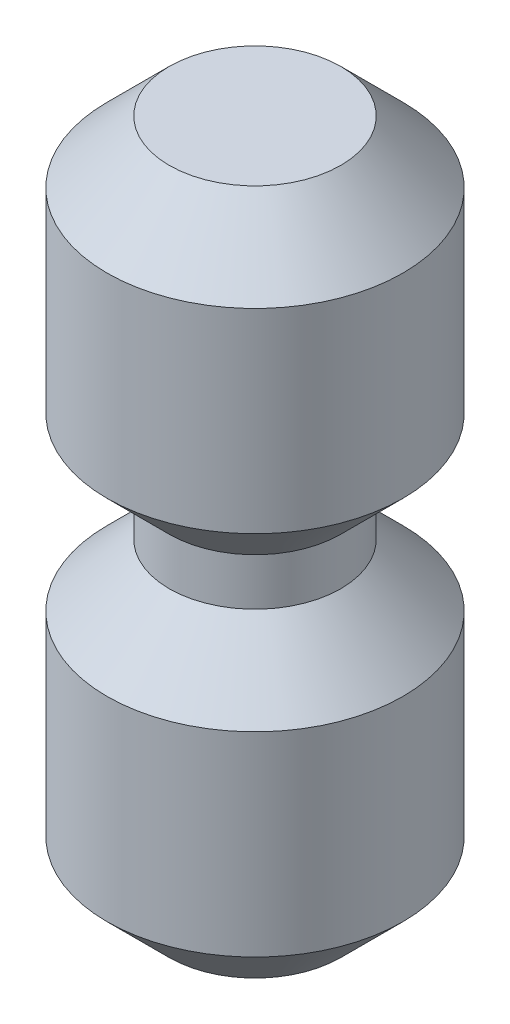
SolidWorks part; units mm, degrees
ref_plane "Front Plane" through (0, 0, 0) normal (0, 0, 1) x (1, 0, 0)
ref_plane "Top Plane" through (0, 0, 0) normal (0, 1, 0) x (1, 0, 0)
ref_plane "Right Plane" through (0, 0, 0) normal (1, 0, 0) x (0, 0, -1)
sketch "Sketch1" plane through (0, 0, 0) normal (0, 0, 1) x (1, 0, 0)
  line L0 (1, 4) -> (1.725, 3.275)
  line L1 (1.725, 3.275) -> (1.725, 1)
  line L2 (0, 0) -> (0, 4426.1383) construction
  line L3 (0, 0) -> (4426.1383, 0) construction
  line L4 (1.725, 1) -> (1, 0.275)
  line L5 (1, 0.275) -> (1, -0.275)
  line L6 (1.725, -1) -> (1, -0.275)
  line L7 (1.725, -3.275) -> (1.725, -1)
  line L8 (1, -4) -> (1.725, -3.275)
  line L9 (1, 4) -> (0, 4)
  line L10 (0, 4) -> (0, -4)
  line L11 (0, -4) -> (1, -4)
  point P11 (1, 0)
  dimension "D1" = 4
  dimension "D2" = 3.45
  dimension "D3" = 45
  dimension "D4" = 1
  dimension "D5" = 45
  dimension "D6" = 2
  dimension "D7" = 2
revolve "Revolve1" add sketch "Sketch1" angle 360 about L2
equation "\"D5@Sketch1\"=\"D3@Sketch1\""
